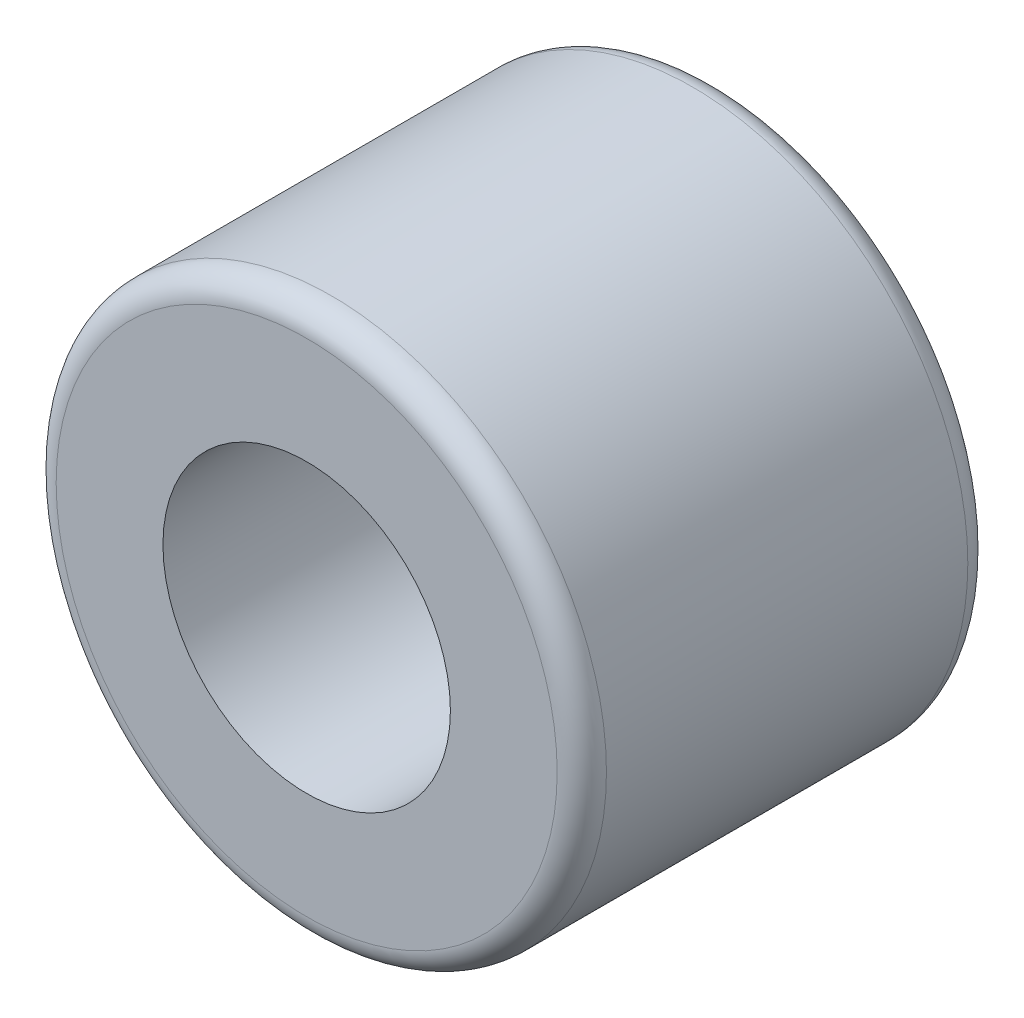
SolidWorks part; units mm, degrees
ref_plane "Front Plane" through (0, 0, 0) normal (0, 0, 1) x (1, 0, 0)
ref_plane "Top Plane" through (0, 0, 0) normal (0, 1, 0) x (1, 0, 0)
ref_plane "Right Plane" through (0, 0, 0) normal (1, 0, 0) x (0, 0, -1)
sketch "Sketch1" plane through (0, 0, 0) normal (0, 0, 1) x (1, 0, 0)
  circle A0 centre (0, 0) radius 8.509
  circle A1 centre (0, 0) radius 4.445
  dimension "D1" = 8.89
  dimension "D2" = 17.018
extrude "Boss-Extrude1" add sketch "Sketch1" along normal blind 12.7
fillet "Fillet1" radius 0.762 2 edges at (8.509, 0, 12.7) (8.509, 0, 0)
